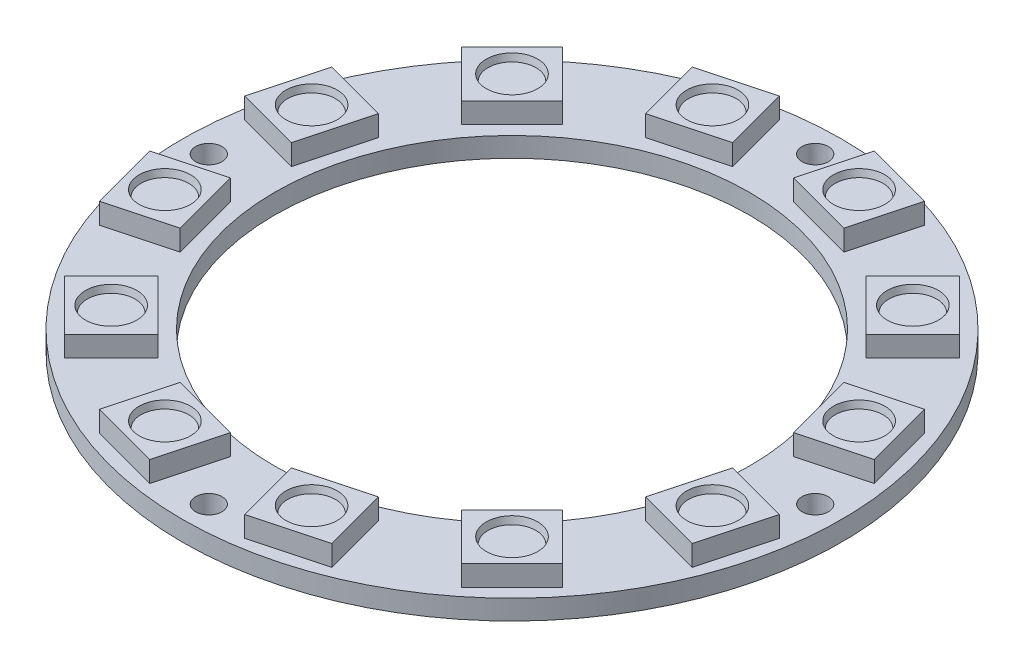
SolidWorks part; units mm, degrees
ref_plane "Plan de face" through (0, 0, 0) normal (0, 0, 1) x (1, 0, 0)
ref_plane "Plan de dessus" through (0, 0, 0) normal (0, 1, 0) x (1, 0, 0)
ref_plane "Plan de droite" through (0, 0, 0) normal (1, 0, 0) x (0, 0, -1)
ref_axis "Axe1" through (0, 0.825, 0) along (0, -1, 0)
sketch "Contour" plane through (0, 0, 0) normal (0, 0, 1) x (1, 0, 0)
  line L0 (55, 0) -> (-55, 0) construction
  line L1 (18, -0.75) -> (25, -0.75)
  line L2 (18, -0.75) -> (18, 0.75)
  line L3 (18, 0.75) -> (25, 0.75)
  line L4 (25, -0.75) -> (25, 0.75)
  line L5 (18, -0.75) -> (25, 0.75) construction
  line L6 (18, 0.75) -> (25, -0.75) construction
  line L7 (0, -55) -> (0, 55) construction
  point P0 (21.5, 0)
  dimension "D1" = 7
  dimension "D2" = 1.5
  dimension "D3" = 18
revolve "Révolution1_Contour" add sketch "Contour" angle 360 about axis through (0, 0.825, 0) along (0, -1, 0)
sketch "RGB_DEL" plane through (0, 0.75, 0) normal (0, 1, 0) x (1, 0, 0)
  line L0 (-13.435, 13.435) -> (0, 0) construction
  line L11 (-15.3442, 11.5258) -> (-11.5258, 15.3442)
  line L12 (-11.5258, 15.3442) -> (-15.0614, 18.8798)
  line L13 (-15.0614, 18.8798) -> (-18.8798, 15.0614)
  line L14 (-18.8798, 15.0614) -> (-15.3442, 11.5258)
  line L15 (0, 0) -> (25, 0) construction
  circle A0 centre (0, 0) radius 25 construction
  dimension "D3" = 19
  dimension "D4" = 5
  dimension "D5" = 5.4
  dimension "D6" = 135
extrude "Boss.-Extru.2_RGB_DEL" add sketch "RGB_DEL" along normal blind 1.57
pattern_circular "Répétition circulaire1_RGB_DEL" count 12 over 360 about axis through (0, 0, 0) along (0, 1, 0) of "Boss.-Extru.2_RGB_DEL"
sketch "Beignets_soudures" plane through (0, -0.75, 0) normal (0, -1, 0) x (-1, 0, 0)
  line L0 (12.5087, 17.8969) -> (14.3048, 16.1008) construction
  line L5 (8.1317, 18.7383) -> (18.7383, 8.1317) construction
  line L11 (18.7383, 8.1317) -> (22.2739, 11.6673) construction
  line L12 (22.2739, 11.6673) -> (11.6673, 22.2739) construction
  line L17 (11.6673, 22.2739) -> (8.1317, 18.7383) construction
  line L23 (11.6673, 22.2739) -> (18.7383, 8.1317) construction
  line L26 (8.1317, 18.7383) -> (22.2739, 11.6673) construction
  line L27 (14.3048, 16.1008) -> (16.1008, 14.3048) construction
  line L28 (16.1008, 14.3048) -> (17.8969, 12.5087) construction
  line L29 (15.2028, 15.2028) -> (0, 0) construction
  line L30 (0, 0) -> (25, 0) construction
  circle A7 centre (12.5087, 17.8969) radius 0.875
  circle A8 centre (14.3048, 16.1008) radius 0.875
  circle A9 centre (16.1008, 14.3048) radius 0.875
  circle A10 centre (17.8969, 12.5087) radius 0.875
  circle A11 centre (0, 0) radius 25 construction
  point P2 (15.2028, 15.2028)
  dimension "D1" = 15
  dimension "D4" = 1.75
  dimension "D5" = 2.54
  dimension "D2" = 5
  dimension "D6" = 21.5
  dimension "D7" = 45
extrude "Boss.-Extru.3_Beignets_soudures" add sketch "Beignets_soudures" along normal blind 0.0348
sketch "Alignement" plane through (0, -0.75, 0) normal (0, -1, 0) x (-1, 0, 0)
  line L3 (12.5087, 17.8969) -> (17.8969, 12.5087) construction
  circle A0 centre (15.2028, 15.2028) radius 2.7 construction
  point P1 (15.2028, 15.2028)
  dimension "D1" = 5.4
sketch "Lentille" plane through (0, 2.32, 0) normal (0, 1, 0) x (1, 0, 0)
  line L0 (-15.0614, 18.8798) -> (-15.3442, 11.5258) construction
  line L1 (-18.8798, 15.0614) -> (-11.5258, 15.3442) construction
  line L2 (-11.5258, 15.3442) -> (-15.0614, 18.8798) construction
  line L3 (-15.3442, 11.5258) -> (-11.5258, 15.3442) construction
  circle A0 centre (-15.2028, 15.2028) radius 1.95
  point P18 (-15.2028, 15.2028)
  dimension "D1" = 3.9
extrude "Enlèv. mat.-Extru.1_Lentille" cut sketch "Lentille" against normal blind 0.5 draft 15
pattern_circular "Répétition circulaire1" count 12 over 360 about axis through (0, 0, 0) along (0, 1, 0) of "Enlèv. mat.-Extru.1_Lentille"
sketch "Tous_Montage_Vis_M2_Anneau_RGB" plane through (0, 0, 0) normal (0, 1, 0) x (1, 0, 0)
  line L0 (0, -23) -> (0, 23) construction
  line L1 (-23, 0) -> (23, 0) construction
  line L2 (-1.7076, 0) -> (1.7076, 0) construction
  circle A0 centre (-23, 0) radius 1
  circle A1 centre (0, 23) radius 1
  circle A2 centre (23, 0) radius 1
  circle A3 centre (0, -23) radius 1
  point P2 (0, 0)
  point P6 (0, 0)
  dimension "D3" = 2
  dimension "D1" = 46
  dimension "D2" = 90
extrude "Enlèv. mat.-Extru.1_Tous_Montage_Vis_M2_Anneau_RGB" cut sketch "Tous_Montage_Vis_M2_Anneau_RGB" against normal mid plane 5
equation "\"D3@Contour\"=36 / 2"
